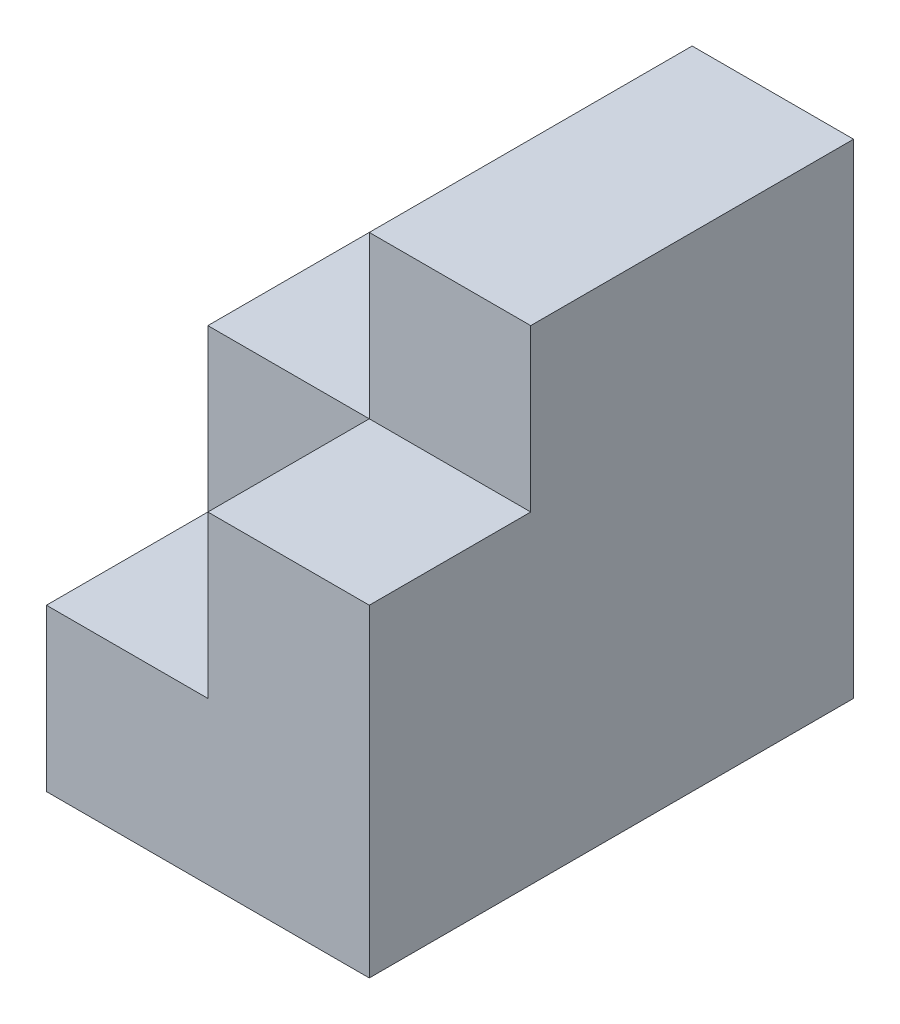
SolidWorks part; units mm, degrees
ref_plane "Plano frontal" through (0, 0, 0) normal (0, 0, 1) x (1, 0, 0)
ref_plane "Plano superior" through (0, 0, 0) normal (0, 1, 0) x (1, 0, 0)
ref_plane "Plano direito" through (0, 0, 0) normal (1, 0, 0) x (0, 0, -1)
sketch "Esboço1" plane through (0, 0, 0) normal (0, 0, 1) x (1, 0, 0)
  line L1 (0, 0) -> (60, 0)
  line L2 (0, 0) -> (0, 20)
  line L3 (0, 20) -> (60, 20)
  line L4 (60, 0) -> (60, 20)
  dimension "D1" = 60
  dimension "D2" = 20
extrude "Ressalto-extrusão1" add sketch "Esboço1" along normal blind 20
sketch "Esboço2" plane through (0, 0, 20) normal (0, 0, 1) x (1, 0, 0)
  line L0 (60, 20) -> (0, 20) construction
  line L1 (60, 0) -> (20, 0)
  line L2 (60, 0) -> (60, 20)
  line L3 (60, 20) -> (20, 20)
  line L4 (20, 0) -> (20, 20)
  dimension "D1" = 40
extrude "Ressalto-extrusão2" add sketch "Esboço2" along normal blind 40
sketch "Esboço3" plane through (0, 20, 0) normal (0, 1, 0) x (1, 0, 0)
  line L0 (60, -60) -> (20, -60) construction
  line L1 (60, 0) -> (40, 0)
  line L2 (60, 0) -> (60, -60)
  line L3 (60, -60) -> (40, -60)
  line L4 (40, 0) -> (40, -60)
extrude "Ressalto-extrusão3" add sketch "Esboço3" along normal blind 20
sketch "Esboço4" plane through (0, 40, 0) normal (0, 1, 0) x (1, 0, 0)
  line L0 (60, -60) -> (60, 0) construction
  line L1 (40, 0) -> (60, 0)
  line L2 (40, 0) -> (40, -40)
  line L3 (40, -40) -> (60, -40)
  line L4 (60, 0) -> (60, -40)
  dimension "D1" = 40
extrude "Ressalto-extrusão4" add sketch "Esboço4" along normal blind 20
